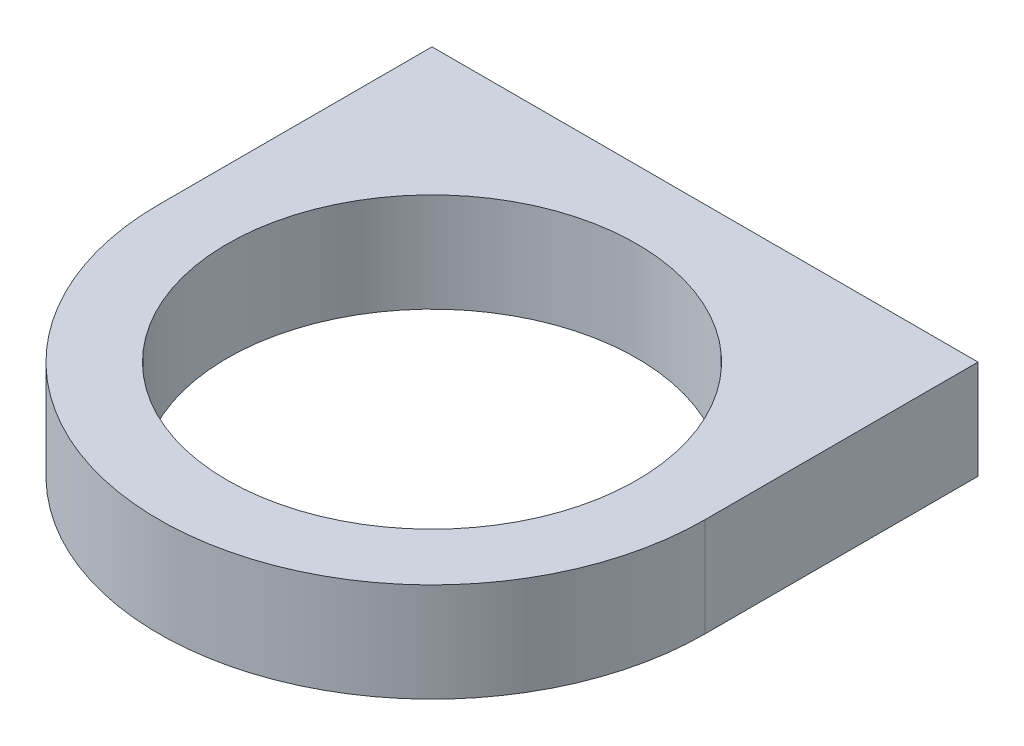
SolidWorks part; units mm, degrees
ref_plane "Alzado" through (0, 0, 0) normal (0, 0, 1) x (1, 0, 0)
ref_plane "Planta" through (0, 0, 0) normal (0, 1, 0) x (1, 0, 0)
ref_plane "Vista lateral" through (0, 0, 0) normal (1, 0, 0) x (0, 0, -1)
sketch "Croquis1" plane through (0, 0, 0) normal (0, 1, 0) x (1, 0, 0)
  line L0 (-40, 0) -> (-40, 40)
  line L1 (-40, 40) -> (40, 40)
  line L2 (40, 40) -> (40, 0)
  arc A0 (-40, 0) -> (40, 0) centre (0, 0) ccw
  dimension "D1" = 40
  dimension "D2" = 40
extrude "Saliente-Extruir1" add sketch "Croquis1" along normal blind 14.5
sketch "Croquis3" plane through (0, 14.5, 0) normal (0, 1, 0) x (1, 0, 0)
  circle A0 centre (0, 0) radius 30
  dimension "D1" = 60
extrude "Cortar-Extruir1" cut sketch "Croquis3" against normal through all
sketch "Croquis4" plane through (0, 0, -40) normal (0, 0, -1) x (-1, 0, 0)
  line L0 (-40, 9.5) -> (-35, 9.5) construction
  line L1 (-40, 14.5) -> (-40, 0) construction
  line L2 (-35, 9.5) -> (-35, 14.5) construction
  line L3 (-40, 14.5) -> (40, 14.5) construction
  line L4 (-40, 5) -> (-35, 5) construction
  line L5 (-35, 5) -> (-35, 0) construction
  line L6 (-40, 0) -> (40, 0) construction
  line L7 (0, 0) -> (0, 22.7052) construction
  line L8 (40, 9.5) -> (35, 9.5) construction
  line L9 (40, 14.5) -> (40, 0) construction
  line L10 (35, 9.5) -> (35, 14.5) construction
  line L11 (40, 5) -> (35, 5) construction
  line L12 (35, 5) -> (35, 0) construction
  circle A0 centre (-35, 9.5) radius 1.35
  circle A1 centre (-35, 5) radius 1.35
  circle A2 centre (35, 9.5) radius 1.35
  circle A3 centre (35, 5) radius 1.35
  dimension "D5" = 2.7
  dimension "D6" = 2.7
  dimension "D11" = 2.7
  dimension "D12" = 2.7
  dimension "D1" = 5
  dimension "D2" = 5
  dimension "D3" = 5
  dimension "D4" = 5
  dimension "D7" = 5
  dimension "D8" = 5
  dimension "D9" = 5
  dimension "D10" = 5
extrude "Cortar-Extruir2" cut sketch "Croquis4" against normal blind 30
